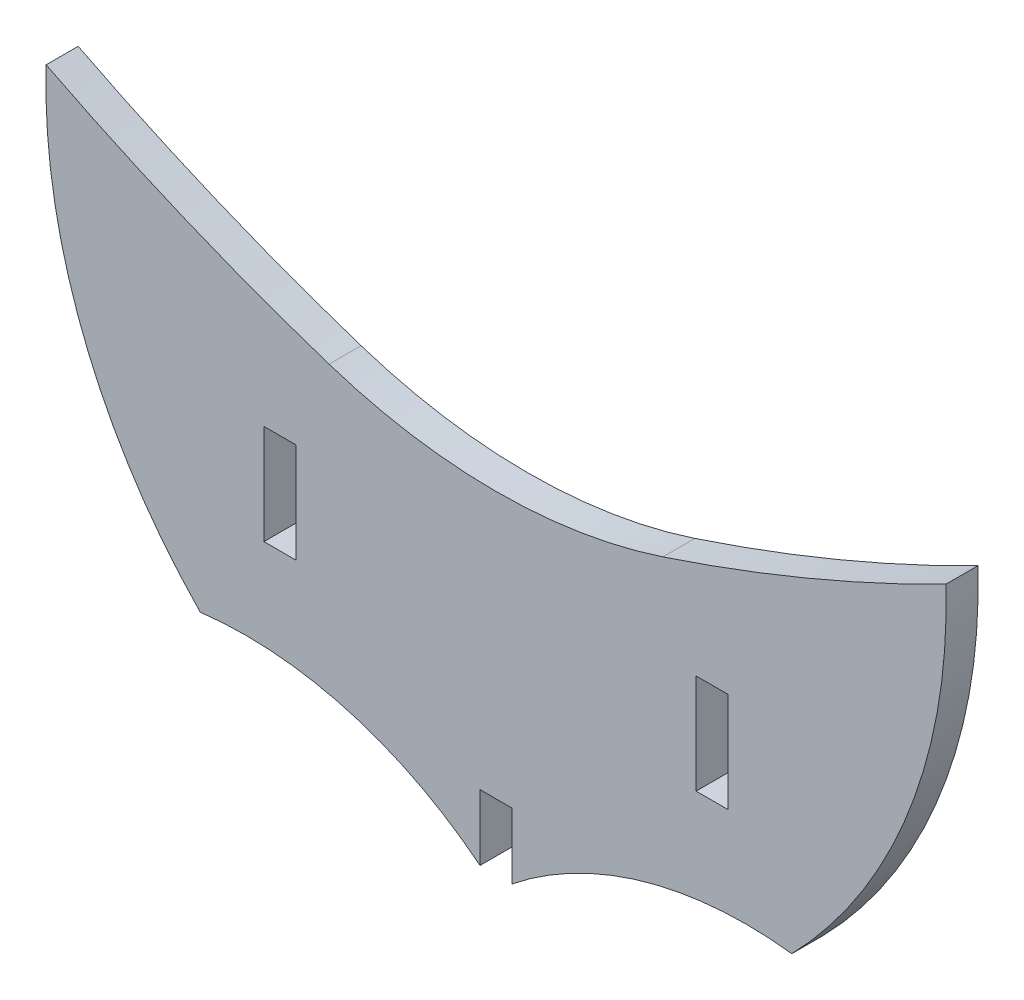
SolidWorks part; units mm, degrees
ref_plane "Front Plane" through (0, 0, 0) normal (0, 0, 1) x (1, 0, 0)
ref_plane "Top Plane" through (0, 0, 0) normal (0, 1, 0) x (1, 0, 0)
ref_plane "Right Plane" through (0, 0, 0) normal (1, 0, 0) x (0, 0, -1)
sketch "Sketch1" plane through (0, 0, 0) normal (0, 0, 1) x (1, 0, 0)
  line L0 (-1.524, 17.1379) -> (-1.524, 14.0091)
  line L3 (-1.524, 17.1379) -> (0, 17.1379)
  line L4 (0, 17.1379) -> (0, 14.0091)
  arc A0 (-22.1769, 36.693) -> (-8.7069, 31.0849) centre (21.1978, 121.894) ccw
  arc A1 (-1.524, 14.0091) -> (-14.842, 17.7934) centre (-12.6704, 0.1091) ccw
  arc A2 (-22.1769, 36.693) -> (-14.842, 17.7934) centre (3.7237, 35.8719) ccw
  arc A3 (20.6529, 36.693) -> (7.1829, 31.0849) centre (-22.7218, 121.894) cw
  arc A4 (20.6529, 36.693) -> (13.318, 17.7934) centre (-5.2477, 35.8719) cw
  arc A5 (0, 14.0091) -> (13.318, 17.7934) centre (11.1464, 0.1091) cw
  arc A6 (7.1829, 31.0849) -> (-8.7069, 31.0849) centre (-0.762, 55.2104) cw
  dimension "D1" = 25.4
extrude "Boss-Extrude1" add sketch "Sketch1" along normal blind 1.524
sketch "Sketch2" plane through (0, 0, 1.524) normal (0, 0, 1) x (1, 0, 0)
  line L0 (-0.762, 17.1379) -> (-0.762, 39.5161) construction
  line L1 (-11.811, 26.9677) -> (-10.287, 26.9677)
  line L2 (-11.811, 26.9677) -> (-11.811, 22.2179)
  line L3 (-11.811, 22.2179) -> (-10.287, 22.2179)
  line L4 (-10.287, 26.9677) -> (-10.287, 22.2179)
  line L5 (-1.524, 17.1379) -> (0, 17.1379) construction
  line L6 (8.763, 26.9677) -> (8.763, 22.2179)
  line L7 (10.287, 22.2179) -> (8.763, 22.2179)
  line L8 (10.287, 26.9677) -> (10.287, 22.2179)
  line L9 (10.287, 26.9677) -> (8.763, 26.9677)
  dimension "D1" = 1.524
  dimension "D2" = 4.7498
  dimension "D3" = 5.08
  dimension "D4" = 9.525
extrude "Cut-Extrude1" cut sketch "Sketch2" against normal blind 2.54
